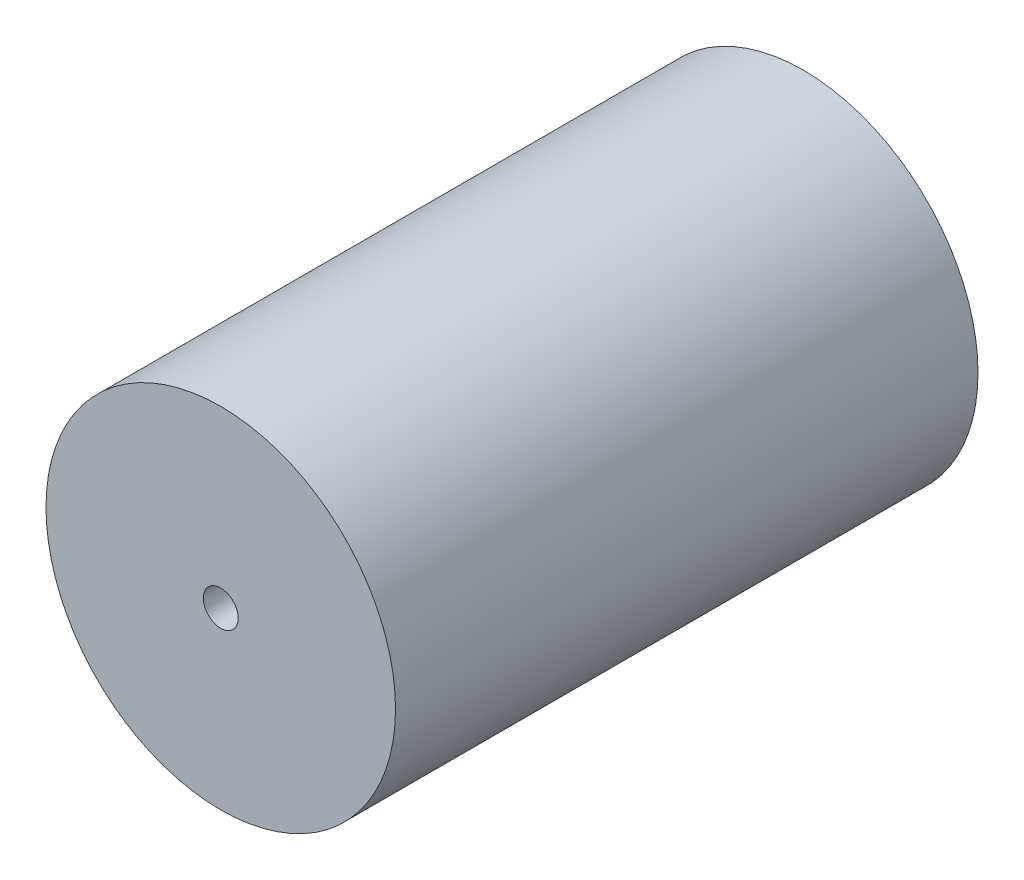
SolidWorks part; units mm, degrees
ref_plane "Front Plane" through (0, 0, 0) normal (0, 0, 1) x (1, 0, 0)
ref_plane "Top Plane" through (0, 0, 0) normal (0, 1, 0) x (1, 0, 0)
ref_plane "Right Plane" through (0, 0, 0) normal (1, 0, 0) x (0, 0, -1)
sketch "Sketch1" plane through (0, 0, 0) normal (0, 0, 1) x (1, 0, 0)
  circle A0 centre (0, 5.6166) radius 15
  circle A1 centre (0, 5.6166) radius 150
  dimension "D1" = 30
  dimension "D2" = 300
extrude "Boss-Extrude1" add sketch "Sketch1" along normal blind 500
